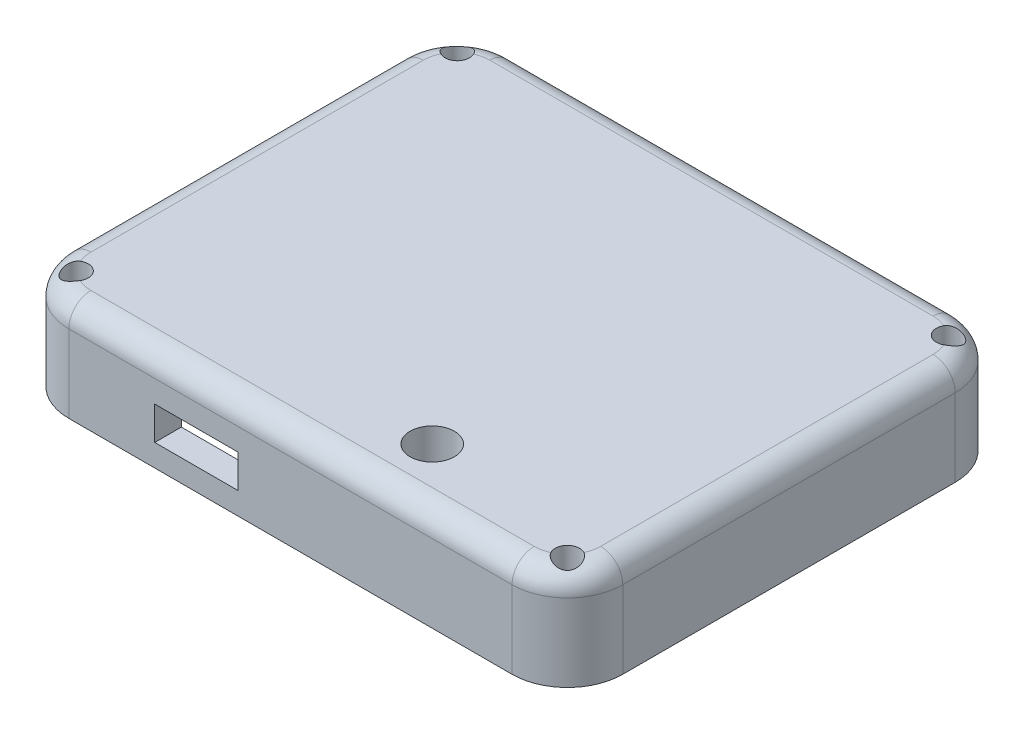
SolidWorks part; units mm, degrees
ref_plane "Front Plane" through (0, 0, 0) normal (0, 0, 1) x (1, 0, 0)
ref_plane "Top Plane" through (0, 0, 0) normal (0, 1, 0) x (1, 0, 0)
ref_plane "Right Plane" through (0, 0, 0) normal (1, 0, 0) x (0, 0, -1)
sketch "Sketch1" plane through (0, 0, 0) normal (0, 1, 0) x (1, 0, 0)
  line L1 (-31.8235, 18.8908) -> (8.1765, 18.8908)
  line L2 (-36.8235, 13.8908) -> (-36.8235, -16.1092)
  line L3 (-31.8235, -21.1092) -> (8.1765, -21.1092)
  line L4 (13.1765, 13.8908) -> (13.1765, -16.1092)
  arc A0 (8.1765, -21.1092) -> (13.1765, -16.1092) centre (8.1765, -16.1092) ccw
  arc A1 (-36.8235, -16.1092) -> (-31.8235, -21.1092) centre (-31.8235, -16.1092) ccw
  arc A2 (-31.8235, 18.8908) -> (-36.8235, 13.8908) centre (-31.8235, 13.8908) ccw
  arc A3 (8.1765, 18.8908) -> (13.1765, 13.8908) centre (8.1765, 13.8908) cw
  point P6 (13.1765, -21.1092)
  point P11 (-36.8235, 18.8908)
  point P14 (13.1765, 18.8908)
  dimension "D3" = 5
  dimension "D1" = 50
  dimension "D2" = 40
extrude "Boss-Extrude1" add sketch "Sketch1" along normal blind 9
fillet "Fillet1" radius 2 8 edges at (-35.3591, 9, 19.6448) (-35.3591, 9, -17.4263) (11.712, 9, -17.4263) (11.712, 9, 19.6448) (-36.8235, 9, 1.1092) (13.1765, 9, 1.1092) (-11.8235, 9, 21.1092) (-11.8235, 9, -18.8908)
sketch "Sketch2" plane through (0, 0, 0) normal (0, -1, 0) x (1, 0, 0)
  line L0 (-36.8235, -13.8908) -> (-36.8235, 16.1092) construction
  line L1 (-29.4235, 18.7092) -> (5.7765, 18.7092)
  line L2 (-34.4235, 13.7092) -> (-34.4235, -11.4908)
  line L3 (-29.4235, -16.4908) -> (5.7765, -16.4908)
  line L4 (10.7765, 13.7092) -> (10.7765, -11.4908)
  line L5 (13.1765, 16.1092) -> (13.1765, -13.8908) construction
  line L6 (-31.8235, 21.1092) -> (8.1765, 21.1092) construction
  line L7 (8.1765, -18.8908) -> (-31.8235, -18.8908) construction
  arc A0 (5.7765, -16.4908) -> (10.7765, -11.4908) centre (5.7765, -11.4908) ccw
  arc A1 (5.7765, 18.7092) -> (10.7765, 13.7092) centre (5.7765, 13.7092) cw
  arc A2 (-29.4235, 18.7092) -> (-34.4235, 13.7092) centre (-29.4235, 13.7092) ccw
  arc A3 (-34.4235, -11.4908) -> (-29.4235, -16.4908) centre (-29.4235, -11.4908) ccw
  dimension "D5" = 5
  dimension "D1" = 2.4
  dimension "D2" = 2.4
  dimension "D3" = 2.4
  dimension "D4" = 2.4
extrude "Cut-Extrude1" cut sketch "Sketch2" against normal blind 7
sketch "Sketch3" plane through (0, 0, 0) normal (0, -1, 0) x (1, 0, 0)
  line L0 (-31.8235, 21.1092) -> (8.1765, 21.1092) construction
  line L1 (13.1765, 16.1092) -> (13.1765, -13.8908) construction
  circle A0 centre (10.3765, 18.3092) radius 1.1
  circle A1 centre (-34.0235, 18.2462) radius 1.1
  circle A2 centre (-34.0235, -16.1538) radius 1.1
  circle A3 centre (10.3765, -16.0908) radius 1.1
  dimension "D1" = 2.2
  dimension "D2" = 2.8
  dimension "D3" = 2.8
  dimension "D4" = 2
  dimension "D5" = 2
extrude "Cut-Extrude2" cut sketch "Sketch3" against normal through all
sketch "Sketch4" plane through (0, 7, 0) normal (0, -1, 0) x (1, 0, 0)
  line L1 (5.7765, 18.7092) -> (-29.4235, 18.7092) construction
  line L2 (10.7765, -11.4908) -> (10.7765, 13.7092) construction
  circle A1 centre (6.2015, 15.8592) radius 1.5
  circle A2 centre (-30.2985, 15.8592) radius 1.5
  circle A3 centre (-30.2985, -13.6408) radius 1.5
  circle A4 centre (6.2015, -13.6408) radius 1.5
  dimension "D1" = 2.85
  dimension "D2" = 4.575
  dimension "D3" = 2
  dimension "D4" = 3
  dimension "D5" = 2
extrude "Boss-Extrude2" add sketch "Sketch4" along normal blind 6
sketch "Sketch5" plane through (0, 1, 0) normal (0, -1, 0) x (1, 0, 0)
  circle A0 centre (6.2015, 15.8592) radius 1.1
  circle A1 centre (6.2015, 15.8592) radius 1.5 construction
  circle A2 centre (-30.2985, 15.8592) radius 1.1
  circle A3 centre (-30.2985, -13.6408) radius 1.1
  circle A4 centre (6.2015, -13.6408) radius 1.1
  dimension "D1" = 2.2
  dimension "D2" = 0
  dimension "D3" = 2
  dimension "D4" = 2
extrude "Cut-Extrude3" cut sketch "Sketch5" against normal blind 5 contours A2 | A3 | A4 | A0
sketch "Sketch7" plane through (0, 7, 0) normal (0, -1, 0) x (-1, 0, 0)
  circle A0 centre (-4.2015, -10.8592) radius 1.2172
  circle A1 centre (-6.2015, -15.8592) radius 1.5 construction
  circle A3 centre (11.7985, -10.8592) radius 1.2172
  circle A4 centre (11.7985, 10.1408) radius 1.2172
  circle A5 centre (-4.2015, 10.1408) radius 1.2172
  dimension "D1" = 2
  dimension "D2" = 5
  dimension "D3" = 2
  dimension "D4" = 2
extrude "Boss-Extrude3" add sketch "Sketch7" along normal blind 3
sketch "Sketch8" plane through (0, 4, 0) normal (0, -1, 0) x (1, 0, 0)
  line L1 (-11.7985, 10.8592) -> (4.2015, 10.8592)
  line L2 (-11.7985, 10.8592) -> (-11.7985, -10.1408)
  line L3 (-11.7985, -10.1408) -> (4.2015, -10.1408)
  line L4 (4.2015, 10.8592) -> (4.2015, -10.1408)
extrude "Cut-Extrude4" cut sketch "Sketch8" against normal blind 3
sketch "Sketch9" plane through (0, 0, -16.4908) normal (0, 0, 1) x (1, 0, 0)
  line L0 (-29.4235, 7) -> (5.7765, 7) construction
  line L1 (-29.4235, 7) -> (-29.4235, 0) construction
  circle A0 centre (-24.4235, 4) radius 2
  dimension "D1" = 4
  dimension "D2" = 3
  dimension "D3" = 5
extrude "Cut-Extrude5" cut sketch "Sketch9" against normal through all
sketch "Sketch10" plane through (0, 7, 0) normal (0, -1, 0) x (1, 0, 0)
  line L0 (5.7765, 18.7092) -> (-29.4235, 18.7092) construction
  line L1 (-34.4235, 13.7092) -> (-34.4235, -11.4908) construction
  circle A0 centre (-4.4235, 15.7092) radius 2.5
  dimension "D1" = 5
  dimension "D2" = 3
  dimension "D3" = 30
extrude "Boss-Extrude4" add sketch "Sketch10" along normal blind 2
sketch "Sketch11" plane through (0, 5, 0) normal (0, -1, 0) x (1, 0, 0)
  circle A0 centre (-4.4235, 15.7092) radius 2
  dimension "D1" = 4
extrude "Cut-Extrude6" cut sketch "Sketch11" against normal through all
sketch "Sketch14" plane through (0, 7, 0) normal (0, -1, 0) x (-1, 0, 0)
  line L1 (-5.7765, -18.7092) -> (29.4235, -18.7092) construction
  circle A0 centre (31.7985, -10.8592) radius 1.1
  arc A2 (10.5814, -10.8592) -> (11.7985, -9.6421) centre (11.7985, -10.8592) ccw construction
  circle A3 centre (31.7985, 4.1408) radius 1.1
  circle A4 centre (12.4985, 4.1408) radius 1.1
  dimension "D1" = 7.85
  dimension "D2" = 20
  dimension "D3" = 2.2
  dimension "D5" = 2.2
  dimension "D6" = 15
  dimension "D7" = 19.3
  dimension "D4" = 2
extrude "Boss-Extrude5" add sketch "Sketch14" along normal blind 3.5
sketch "Sketch15" plane through (0, 3.5, 0) normal (0, -1, 0) x (1, 0, 0)
  line L1 (-31.7985, 10.8592) -> (-12.7985, 10.8592)
  line L2 (-31.7985, 10.8592) -> (-31.7985, -4.1408)
  line L3 (-31.7985, -4.1408) -> (-12.7985, -4.1408)
  line L4 (-12.7985, 10.8592) -> (-12.7985, -4.1408)
  arc A0 (-10.5814, 10.8592) -> (-11.7985, 9.6421) centre (-11.7985, 10.8592) ccw construction
  dimension "D1" = 1
  dimension "D2" = 15
extrude "Cut-Extrude7" cut sketch "Sketch15" against normal blind 3.5
sketch "Sketch16" plane through (0, 3.5, 0) normal (0, -1, 0) x (1, 0, 0)
  line L1 (-11.7985, 10.8592) -> (-10.5814, 10.8592)
  line L2 (-11.7985, 10.8592) -> (-11.7985, -5.987)
  line L3 (-11.7985, -5.987) -> (-10.5814, -5.987)
  line L4 (-10.5814, 10.8592) -> (-10.5814, -5.987)
extrude "Cut-Extrude8" cut sketch "Sketch16" against normal blind 3.5
sketch "Sketch17" plane through (0, 0, 21.1092) normal (0, 0, 1) x (1, 0, 0)
  line L0 (-31.8235, 0) -> (8.1765, 0) construction
  line L1 (-24.0668, 5) -> (-16.5668, 5)
  line L2 (-24.0668, 5) -> (-24.0668, 2)
  line L3 (-24.0668, 2) -> (-16.5668, 2)
  line L4 (-16.5668, 5) -> (-16.5668, 2)
  dimension "D1" = 3
  dimension "D2" = 7.5
  dimension "D3" = 2
extrude "Cut-Extrude9" cut sketch "Sketch17" against normal blind 2.4
